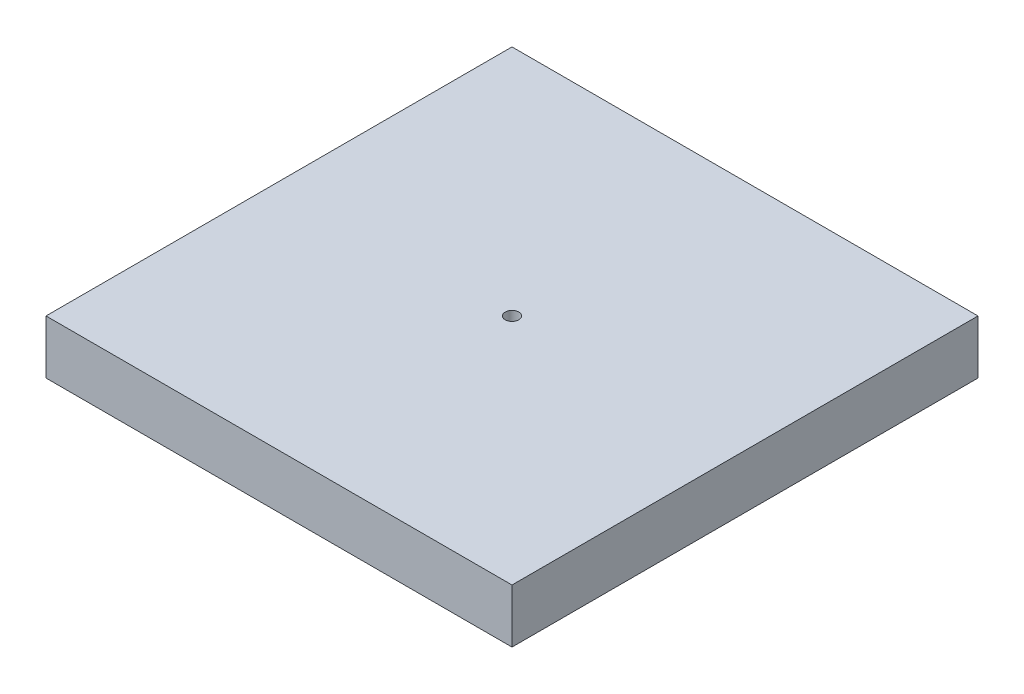
SolidWorks part; units mm, degrees
ref_plane "Front Plane" through (0, 0, 0) normal (0, 0, 1) x (1, 0, 0)
ref_plane "Top Plane" through (0, 0, 0) normal (0, 1, 0) x (1, 0, 0)
ref_plane "Right Plane" through (0, 0, 0) normal (1, 0, 0) x (0, 0, -1)
sketch "Sketch1" plane through (0, 0, 0) normal (0, 1, 0) x (1, 0, 0)
  line L1 (-96.8059, 95.4973) -> (123.1941, 95.4973)
  line L2 (-96.8059, 95.4973) -> (-96.8059, -124.5027)
  line L3 (-96.8059, -124.5027) -> (123.1941, -124.5027)
  line L4 (123.1941, 95.4973) -> (123.1941, -124.5027)
extrude "Boss-Extrude1" add sketch "Sketch1" along normal blind 25.4
sketch "Sketch2" plane through (0, 25.4, 0) normal (0, 1, 0) x (1, 0, 0)
  circle A0 centre (13.1941, -14.5027) radius 3.2
extrude "Cut-Extrude1" cut sketch "Sketch2" against normal blind 25.4
